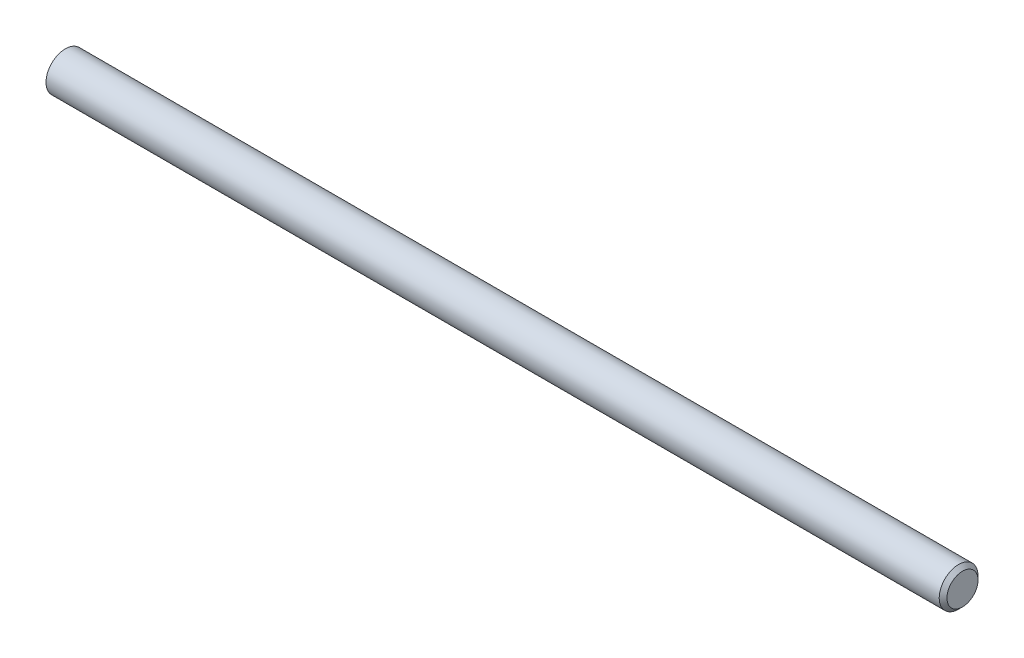
SolidWorks part; units mm, degrees
ref_plane "Alzado" through (0, 0, 0) normal (0, 0, 1) x (1, 0, 0)
ref_plane "Planta" through (0, 0, 0) normal (0, 1, 0) x (1, 0, 0)
ref_plane "Vista lateral" through (0, 0, 0) normal (1, 0, 0) x (0, 0, -1)
sketch "Croquis1" plane through (0, 0, 0) normal (0, 1, 0) x (1, 0, 0)
  line L0 (0, 0) -> (185, 0)
  line L1 (185, 0) -> (185, 3.2)
  line L2 (185, 3.2) -> (184.2, 4)
  line L3 (184.2, 4) -> (0, 4)
  line L4 (0, 4) -> (0, 0)
  dimension "D1" = 185
  dimension "D2" = 3.2
  dimension "D3" = 4
  dimension "D4" = 184.2
revolve "Revolución1" add sketch "Croquis1" angle 360 about L0
